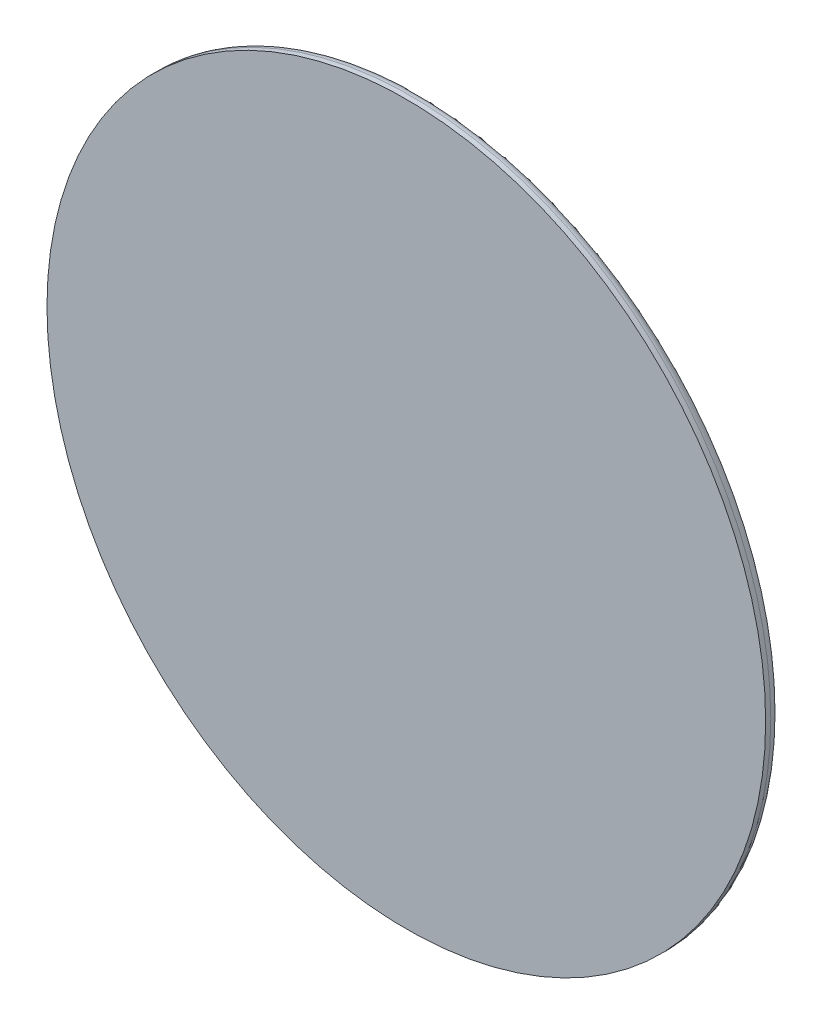
SolidWorks part; units mm, degrees
ref_plane "Front Plane" through (0, 0, 0) normal (0, 0, 1) x (1, 0, 0)
ref_plane "Top Plane" through (0, 0, 0) normal (0, 1, 0) x (1, 0, 0)
ref_plane "Right Plane" through (0, 0, 0) normal (1, 0, 0) x (0, 0, -1)
sketch "Sketch2" plane through (0, 0, 0) normal (0, 0, 1) x (1, 0, 0)
  line L0 (-350, 0) -> (350, 0)
  line L1 (0, 0) -> (0, 350)
  circle A0 centre (0, 0) radius 300
  circle A1 centre (0, 0) radius 350
  circle A2 centre (300, 0) radius 8.89
  circle A3 centre (-300, 0) radius 8.89
  circle A4 centre (0, 300) radius 8.89
extrude "Boss-Extrude1" add sketch "Sketch2" along normal blind 15 contours A3 A0 A2 L0 | A4 A0 A3 L0 L1 | A4 L1 L0 A2 A0 | A3 L0 A1 A2 A0 | A4 A0 A2 L0 A1 L1 | A4 L1 A1 L0 A3 A0
fillet "Fillet1" radius 10 4 edges at (308.89, 0, 0) (8.89, 300, 0) (-291.11, 0, 0) (350, 0, 0)
sketch "Sketch4" plane through (0, 0, 15) normal (0, 0, 1) x (1, 0, 0)
  circle A0 centre (0, 300) radius 8.89
  circle A1 centre (300, 0) radius 8.89
  circle A2 centre (-300, 0) radius 8.89
extrude "Boss-Extrude2" add sketch "Sketch4" against normal blind 1
sketch "Sketch5" plane through (0, 0, 0) normal (0, 0, -1) x (-1, 0, 0)
  line L0 (-340, 0) -> (340, 0)
  line L1 (0, 15.9851) -> (0, 340)
  circle A0 centre (0, 0) radius 340 construction
